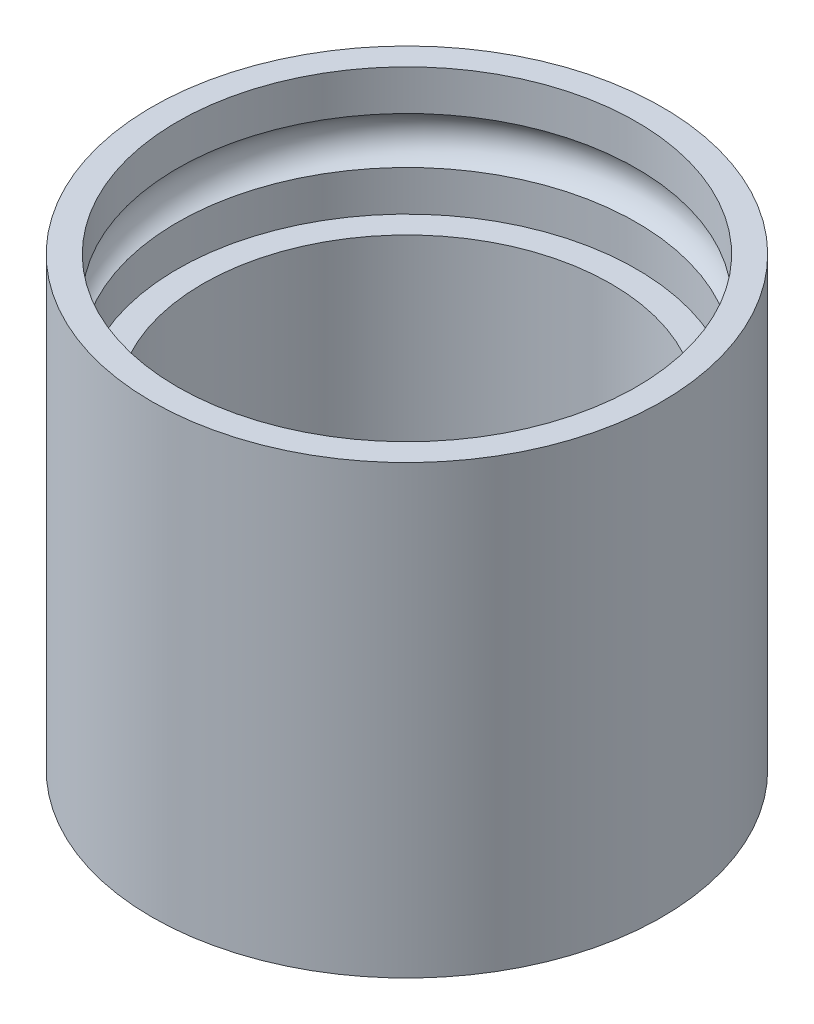
SolidWorks part; units mm, degrees
ref_plane "Front Plane" through (0, 0, 0) normal (0, 0, 1) x (1, 0, 0)
ref_plane "Top Plane" through (0, 0, 0) normal (0, 1, 0) x (1, 0, 0)
ref_plane "Right Plane" through (0, 0, 0) normal (1, 0, 0) x (0, 0, -1)
sketch "Sketch1" plane through (0, 0, 0) normal (1, 0, 0) x (0, 0, -1)
  line L0 (0, 0) -> (0, -88.9)
  line L1 (0, -88.9) -> (10.16, -88.9)
  line L2 (10.16, -76.2) -> (10.16, -25.4)
  line L3 (10.16, -25.4) -> (5.08, -25.4)
  line L4 (5.08, -25.4) -> (5.08, -17.3559)
  line L5 (5.08, -8.0441) -> (5.08, 0)
  line L6 (5.08, 0) -> (0, 0)
  line L7 (50.8, -28.3132) -> (50.8, -103.0735) construction
  line L9 (10.16, -76.2) -> (17.78, -76.2)
  line L10 (17.78, -76.2) -> (17.78, -88.9)
  line L11 (17.78, -88.9) -> (10.16, -88.9)
  arc A0 (5.08, -17.3559) -> (5.08, -8.0441) centre (7.112, -12.7) cw
  point P16 (0, 0)
  point P17 (0, 0)
  dimension "D1" = 88.9
  dimension "D6" = 5.08
  dimension "D2" = 63.5
  dimension "D3" = 5.08
  dimension "D4" = 12.7
  dimension "D5" = 10.16
  dimension "D7" = 50.8
  dimension "D8" = 5.08
  dimension "D9" = 7.62
  dimension "D10" = 12.7
  dimension "D11" = 2.032
revolve "Revolve1" add sketch "Sketch1" angle 360 about L7
